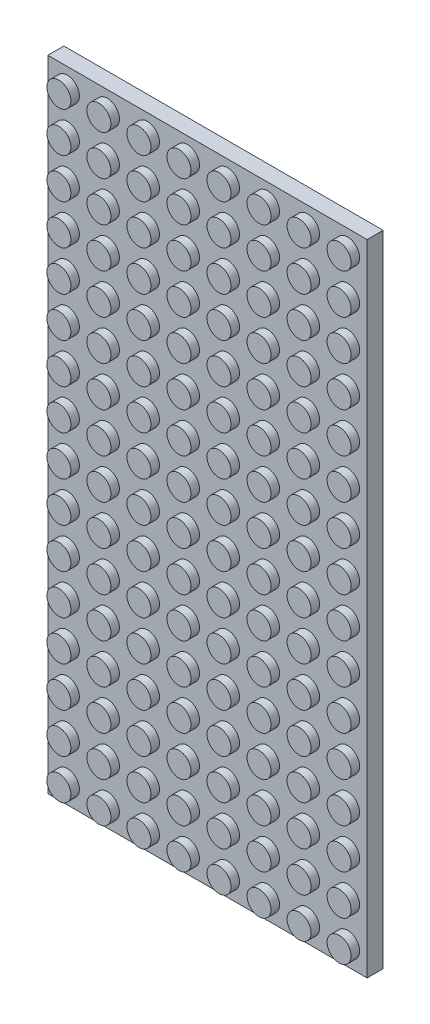
SolidWorks part; units mm, degrees
ref_plane "Спереди" through (0, 0, 0) normal (0, 0, 1) x (1, 0, 0)
ref_plane "Сверху" through (0, 0, 0) normal (0, 1, 0) x (1, 0, 0)
ref_plane "Справа" through (0, 0, 0) normal (1, 0, 0) x (0, 0, -1)
sketch "Эскиз1" plane through (0, 0, 0) normal (0, 0, 1) x (1, 0, 0)
  line L1 (-31.9, -63.9) -> (31.9, -63.9)
  line L2 (-31.9, -63.9) -> (-31.9, 63.9)
  line L3 (-31.9, 63.9) -> (31.9, 63.9)
  line L4 (31.9, -63.9) -> (31.9, 63.9)
  line L5 (-31.9, -63.9) -> (31.9, 63.9) construction
  line L6 (-31.9, 63.9) -> (31.9, -63.9) construction
  point P0 (0, 0)
  dimension "D1" = 63.8
  dimension "D2" = 127.8
extrude "Бобышка-Вытянуть1" add sketch "Эскиз1" along normal blind 3.2
sketch "Эскиз2" plane through (0, 0, 3.2) normal (0, 0, 1) x (1, 0, 0)
  line L0 (-31.9, 63.9) -> (-31.9, -63.9) construction
  line L1 (31.9, 63.9) -> (-31.9, 63.9) construction
  circle A0 centre (-28, 60) radius 2.4
  circle A1 centre (-20, 60) radius 2.4
  circle A2 centre (-12, 60) radius 2.4
  circle A3 centre (-4, 60) radius 2.4
  circle A4 centre (4, 60) radius 2.4
  circle A5 centre (12, 60) radius 2.4
  circle A6 centre (20, 60) radius 2.4
  circle A7 centre (28, 60) radius 2.4
  circle A8 centre (-20, 52) radius 2.4
  circle A9 centre (-12, 52) radius 2.4
  circle A10 centre (-4, 52) radius 2.4
  circle A11 centre (4, 52) radius 2.4
  circle A12 centre (12, 52) radius 2.4
  circle A13 centre (20, 52) radius 2.4
  circle A14 centre (28, 52) radius 2.4
  circle A15 centre (-20, 44) radius 2.4
  circle A16 centre (-12, 44) radius 2.4
  circle A17 centre (-4, 44) radius 2.4
  circle A18 centre (4, 44) radius 2.4
  circle A19 centre (12, 44) radius 2.4
  circle A20 centre (20, 44) radius 2.4
  circle A21 centre (28, 44) radius 2.4
  circle A22 centre (-20, 36) radius 2.4
  circle A23 centre (-12, 36) radius 2.4
  circle A24 centre (-4, 36) radius 2.4
  circle A25 centre (4, 36) radius 2.4
  circle A26 centre (12, 36) radius 2.4
  circle A27 centre (20, 36) radius 2.4
  circle A28 centre (28, 36) radius 2.4
  circle A29 centre (-20, 28) radius 2.4
  circle A30 centre (-12, 28) radius 2.4
  circle A31 centre (-4, 28) radius 2.4
  circle A32 centre (4, 28) radius 2.4
  circle A33 centre (12, 28) radius 2.4
  circle A34 centre (20, 28) radius 2.4
  circle A35 centre (28, 28) radius 2.4
  circle A36 centre (-20, 20) radius 2.4
  circle A37 centre (-12, 20) radius 2.4
  circle A38 centre (-4, 20) radius 2.4
  circle A39 centre (4, 20) radius 2.4
  circle A40 centre (12, 20) radius 2.4
  circle A41 centre (20, 20) radius 2.4
  circle A42 centre (28, 20) radius 2.4
  circle A43 centre (-20, 12) radius 2.4
  circle A44 centre (-12, 12) radius 2.4
  circle A45 centre (-4, 12) radius 2.4
  circle A46 centre (4, 12) radius 2.4
  circle A47 centre (12, 12) radius 2.4
  circle A48 centre (20, 12) radius 2.4
  circle A49 centre (28, 12) radius 2.4
  circle A50 centre (-20, 4) radius 2.4
  circle A51 centre (-12, 4) radius 2.4
  circle A52 centre (-4, 4) radius 2.4
  circle A53 centre (4, 4) radius 2.4
  circle A54 centre (12, 4) radius 2.4
  circle A55 centre (20, 4) radius 2.4
  circle A56 centre (28, 4) radius 2.4
  circle A57 centre (-20, -4) radius 2.4
  circle A58 centre (-12, -4) radius 2.4
  circle A59 centre (-4, -4) radius 2.4
  circle A60 centre (4, -4) radius 2.4
  circle A61 centre (12, -4) radius 2.4
  circle A62 centre (20, -4) radius 2.4
  circle A63 centre (28, -4) radius 2.4
  circle A64 centre (-20, -12) radius 2.4
  circle A65 centre (-12, -12) radius 2.4
  circle A66 centre (-4, -12) radius 2.4
  circle A67 centre (4, -12) radius 2.4
  circle A68 centre (12, -12) radius 2.4
  circle A69 centre (20, -12) radius 2.4
  circle A70 centre (28, -12) radius 2.4
  circle A71 centre (-20, -20) radius 2.4
  circle A72 centre (-12, -20) radius 2.4
  circle A73 centre (-4, -20) radius 2.4
  circle A74 centre (4, -20) radius 2.4
  circle A75 centre (12, -20) radius 2.4
  circle A76 centre (20, -20) radius 2.4
  circle A77 centre (28, -20) radius 2.4
  circle A78 centre (-20, -28) radius 2.4
  circle A79 centre (-12, -28) radius 2.4
  circle A80 centre (-4, -28) radius 2.4
  circle A81 centre (4, -28) radius 2.4
  circle A82 centre (12, -28) radius 2.4
  circle A83 centre (20, -28) radius 2.4
  circle A84 centre (28, -28) radius 2.4
  circle A85 centre (-20, -36) radius 2.4
  circle A86 centre (-12, -36) radius 2.4
  circle A87 centre (-4, -36) radius 2.4
  circle A88 centre (4, -36) radius 2.4
  circle A89 centre (12, -36) radius 2.4
  circle A90 centre (20, -36) radius 2.4
  circle A91 centre (28, -36) radius 2.4
  circle A92 centre (-20, -44) radius 2.4
  circle A93 centre (-12, -44) radius 2.4
  circle A94 centre (-4, -44) radius 2.4
  circle A95 centre (4, -44) radius 2.4
  circle A96 centre (12, -44) radius 2.4
  circle A97 centre (20, -44) radius 2.4
  circle A98 centre (28, -44) radius 2.4
  circle A99 centre (-20, -52) radius 2.4
  circle A100 centre (-12, -52) radius 2.4
  circle A101 centre (-4, -52) radius 2.4
  circle A102 centre (4, -52) radius 2.4
  circle A103 centre (12, -52) radius 2.4
  circle A104 centre (20, -52) radius 2.4
  circle A105 centre (28, -52) radius 2.4
  circle A106 centre (-20, -60) radius 2.4
  circle A107 centre (-12, -60) radius 2.4
  circle A108 centre (-4, -60) radius 2.4
  circle A109 centre (4, -60) radius 2.4
  circle A110 centre (12, -60) radius 2.4
  circle A111 centre (20, -60) radius 2.4
  circle A112 centre (28, -60) radius 2.4
  circle A113 centre (-28, 52) radius 2.4
  circle A114 centre (-28, 44) radius 2.4
  circle A115 centre (-28, 36) radius 2.4
  circle A116 centre (-28, 28) radius 2.4
  circle A117 centre (-28, 20) radius 2.4
  circle A118 centre (-28, 12) radius 2.4
  circle A119 centre (-28, 4) radius 2.4
  circle A120 centre (-28, -4) radius 2.4
  circle A121 centre (-28, -12) radius 2.4
  circle A122 centre (-28, -20) radius 2.4
  circle A123 centre (-28, -28) radius 2.4
  circle A124 centre (-28, -36) radius 2.4
  circle A125 centre (-28, -44) radius 2.4
  circle A126 centre (-28, -52) radius 2.4
  circle A127 centre (-28, -60) radius 2.4
  dimension "D1" = 3.9
  dimension "D2" = 3.9
  dimension "D3" = 8
  dimension "D4" = 16
extrude "Бобышка-Вытянуть2" add sketch "Эскиз2" along normal blind 1.7
sketch "Эскиз3" plane through (0, 0, 0) normal (0, 0, -1) x (-1, 0, 0)
  line L0 (-31.9, 63.9) -> (31.9, 63.9) construction
  line L1 (-31.9, -63.9) -> (-31.9, 63.9) construction
  circle A0 centre (-28, 60) radius 2.5
  circle A1 centre (-20, 60) radius 2.5
  circle A2 centre (-12, 60) radius 2.5
  circle A3 centre (-4, 60) radius 2.5
  circle A4 centre (4, 60) radius 2.5
  circle A5 centre (12, 60) radius 2.5
  circle A6 centre (20, 60) radius 2.5
  circle A7 centre (28, 60) radius 2.5
  circle A8 centre (-20, 52) radius 2.5
  circle A9 centre (-12, 52) radius 2.5
  circle A10 centre (-4, 52) radius 2.5
  circle A11 centre (4, 52) radius 2.5
  circle A12 centre (12, 52) radius 2.5
  circle A13 centre (20, 52) radius 2.5
  circle A14 centre (28, 52) radius 2.5
  circle A15 centre (-20, 44) radius 2.5
  circle A16 centre (-12, 44) radius 2.5
  circle A17 centre (-4, 44) radius 2.5
  circle A18 centre (4, 44) radius 2.5
  circle A19 centre (12, 44) radius 2.5
  circle A20 centre (20, 44) radius 2.5
  circle A21 centre (28, 44) radius 2.5
  circle A22 centre (-20, 36) radius 2.5
  circle A23 centre (-12, 36) radius 2.5
  circle A24 centre (-4, 36) radius 2.5
  circle A25 centre (4, 36) radius 2.5
  circle A26 centre (12, 36) radius 2.5
  circle A27 centre (20, 36) radius 2.5
  circle A28 centre (28, 36) radius 2.5
  circle A29 centre (-20, 28) radius 2.5
  circle A30 centre (-12, 28) radius 2.5
  circle A31 centre (-4, 28) radius 2.5
  circle A32 centre (4, 28) radius 2.5
  circle A33 centre (12, 28) radius 2.5
  circle A34 centre (20, 28) radius 2.5
  circle A35 centre (28, 28) radius 2.5
  circle A36 centre (-20, 20) radius 2.5
  circle A37 centre (-12, 20) radius 2.5
  circle A38 centre (-4, 20) radius 2.5
  circle A39 centre (4, 20) radius 2.5
  circle A40 centre (12, 20) radius 2.5
  circle A41 centre (20, 20) radius 2.5
  circle A42 centre (28, 20) radius 2.5
  circle A43 centre (-20, 12) radius 2.5
  circle A44 centre (-12, 12) radius 2.5
  circle A45 centre (-4, 12) radius 2.5
  circle A46 centre (4, 12) radius 2.5
  circle A47 centre (12, 12) radius 2.5
  circle A48 centre (20, 12) radius 2.5
  circle A49 centre (28, 12) radius 2.5
  circle A50 centre (-20, 4) radius 2.5
  circle A51 centre (-12, 4) radius 2.5
  circle A52 centre (-4, 4) radius 2.5
  circle A53 centre (4, 4) radius 2.5
  circle A54 centre (12, 4) radius 2.5
  circle A55 centre (20, 4) radius 2.5
  circle A56 centre (28, 4) radius 2.5
  circle A57 centre (-20, -4) radius 2.5
  circle A58 centre (-12, -4) radius 2.5
  circle A59 centre (-4, -4) radius 2.5
  circle A60 centre (4, -4) radius 2.5
  circle A61 centre (12, -4) radius 2.5
  circle A62 centre (20, -4) radius 2.5
  circle A63 centre (28, -4) radius 2.5
  circle A64 centre (-20, -12) radius 2.5
  circle A65 centre (-12, -12) radius 2.5
  circle A66 centre (-4, -12) radius 2.5
  circle A67 centre (4, -12) radius 2.5
  circle A68 centre (12, -12) radius 2.5
  circle A69 centre (20, -12) radius 2.5
  circle A70 centre (28, -12) radius 2.5
  circle A71 centre (-20, -20) radius 2.5
  circle A72 centre (-12, -20) radius 2.5
  circle A73 centre (-4, -20) radius 2.5
  circle A74 centre (4, -20) radius 2.5
  circle A75 centre (12, -20) radius 2.5
  circle A76 centre (20, -20) radius 2.5
  circle A77 centre (28, -20) radius 2.5
  circle A78 centre (-20, -28) radius 2.5
  circle A79 centre (-12, -28) radius 2.5
  circle A80 centre (-4, -28) radius 2.5
  circle A81 centre (4, -28) radius 2.5
  circle A82 centre (12, -28) radius 2.5
  circle A83 centre (20, -28) radius 2.5
  circle A84 centre (28, -28) radius 2.5
  circle A85 centre (-20, -36) radius 2.5
  circle A86 centre (-12, -36) radius 2.5
  circle A87 centre (-4, -36) radius 2.5
  circle A88 centre (4, -36) radius 2.5
  circle A89 centre (12, -36) radius 2.5
  circle A90 centre (20, -36) radius 2.5
  circle A91 centre (28, -36) radius 2.5
  circle A92 centre (-20, -44) radius 2.5
  circle A93 centre (-12, -44) radius 2.5
  circle A94 centre (-4, -44) radius 2.5
  circle A95 centre (4, -44) radius 2.5
  circle A96 centre (12, -44) radius 2.5
  circle A97 centre (20, -44) radius 2.5
  circle A98 centre (28, -44) radius 2.5
  circle A99 centre (-20, -52) radius 2.5
  circle A100 centre (-12, -52) radius 2.5
  circle A101 centre (-4, -52) radius 2.5
  circle A102 centre (4, -52) radius 2.5
  circle A103 centre (12, -52) radius 2.5
  circle A104 centre (20, -52) radius 2.5
  circle A105 centre (28, -52) radius 2.5
  circle A106 centre (-20, -60) radius 2.5
  circle A107 centre (-12, -60) radius 2.5
  circle A108 centre (-4, -60) radius 2.5
  circle A109 centre (4, -60) radius 2.5
  circle A110 centre (12, -60) radius 2.5
  circle A111 centre (20, -60) radius 2.5
  circle A112 centre (28, -60) radius 2.5
  circle A113 centre (-28, 52) radius 2.5
  circle A114 centre (-28, 44) radius 2.5
  circle A115 centre (-28, 36) radius 2.5
  circle A116 centre (-28, 28) radius 2.5
  circle A117 centre (-28, 20) radius 2.5
  circle A118 centre (-28, 12) radius 2.5
  circle A119 centre (-28, 4) radius 2.5
  circle A120 centre (-28, -4) radius 2.5
  circle A121 centre (-28, -12) radius 2.5
  circle A122 centre (-28, -20) radius 2.5
  circle A123 centre (-28, -28) radius 2.5
  circle A124 centre (-28, -36) radius 2.5
  circle A125 centre (-28, -44) radius 2.5
  circle A126 centre (-28, -52) radius 2.5
  circle A127 centre (-28, -60) radius 2.5
  dimension "D1" = 3.9
  dimension "D2" = 3.9
  dimension "D3" = 8
  dimension "D4" = 16
extrude "Вырез-Вытянуть1" cut sketch "Эскиз3" against normal blind 1.8
